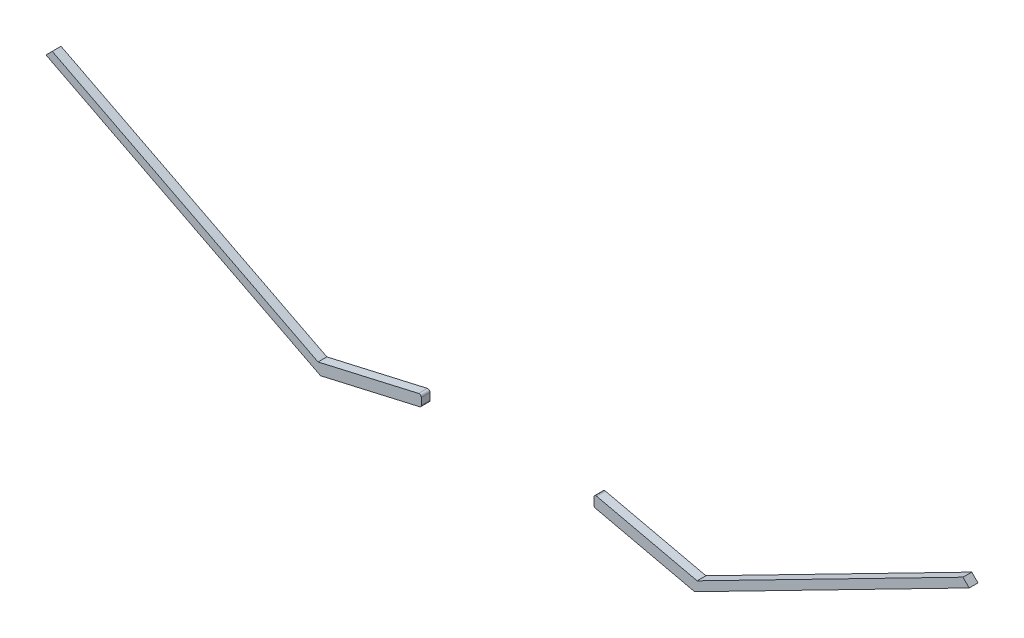
SolidWorks part; units mm, degrees
ref_plane "정면" through (0, 0, 0) normal (0, 0, 1) x (1, 0, 0)
ref_plane "윗면" through (0, 0, 0) normal (0, 1, 0) x (1, 0, 0)
ref_plane "우측면" through (0, 0, 0) normal (1, 0, 0) x (0, 0, -1)
sketch "스케치1" plane through (0, 0, 0) normal (0, 0, 1) x (1, 0, 0)
  line L0 (-103.4853, 16.6769) -> (-43.0759, -14.2441)
  line L1 (-43.0759, -14.2441) -> (-20.2231, -9.0126)
  line L2 (-19.6116, -9.5) -> (-19.6116, -11.0388)
  line L3 (-20, -11.5262) -> (-42.5, -16.6769)
  line L4 (-42.5, -16.6769) -> (-104.8995, 15.2627)
  line L5 (-104.8995, 15.2627) -> (-103.4853, 16.6769)
  line L6 (104.8995, 15.2627) -> (103.4853, 16.6769)
  line L7 (42.5, -16.6769) -> (104.8995, 15.2627)
  line L8 (20, -11.5262) -> (42.5, -16.6769)
  line L9 (19.6116, -9.5) -> (19.6116, -11.0388)
  line L10 (43.0759, -14.2441) -> (20.2231, -9.0126)
  line L11 (103.4853, 16.6769) -> (43.0759, -14.2441)
  arc A0 (-19.6116, -11.0388) -> (-20, -11.5262) centre (-20.1116, -11.0388) cw
  arc A1 (-20.2231, -9.0126) -> (-19.6116, -9.5) centre (-20.1116, -9.5) cw
  arc A2 (20.2231, -9.0126) -> (19.6116, -9.5) centre (20.1116, -9.5) ccw
  arc A3 (19.6116, -11.0388) -> (20, -11.5262) centre (20.1116, -11.0388) ccw
  dimension "D1" = 0.5
  dimension "D2" = 85
  dimension "D3" = 40
  dimension "D4" = 2
  dimension "D5" = 2.5
  dimension "D6" = 140
extrude "보스-돌출1" add sketch "스케치1" along normal blind 2
